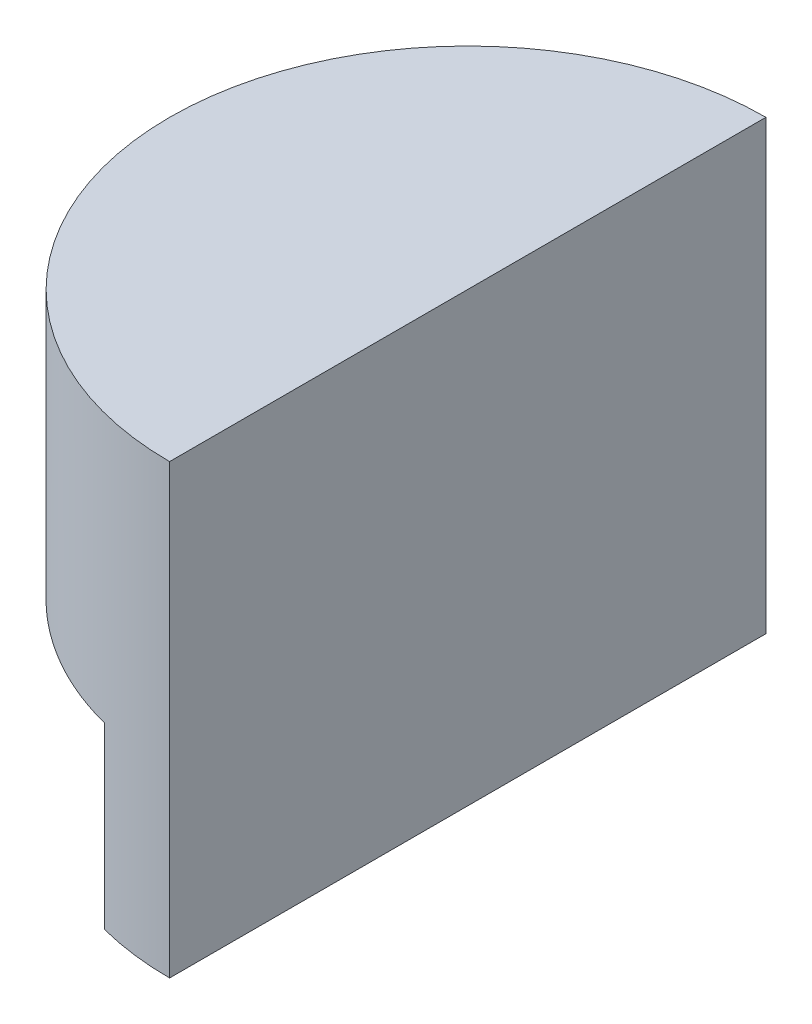
SolidWorks part; units mm, degrees
ref_plane "Alzado" through (0, 0, 0) normal (0, 0, 1) x (1, 0, 0)
ref_plane "Planta" through (0, 0, 0) normal (0, 1, 0) x (1, 0, 0)
ref_plane "Vista lateral" through (0, 0, 0) normal (1, 0, 0) x (0, 0, -1)
sketch "Croquis1" plane through (0, 0, 0) normal (0, 1, 0) x (1, 0, 0)
  line L0 (0, 10) -> (0, -10)
  arc A0 (0, 10) -> (0, -10) centre (0, 0) ccw
  point P3 (0, 0)
  dimension "D1" = 20
extrude "Saliente-Extruir1" add sketch "Croquis1" along normal blind 15
ref_plane "Plano1" through (0, 0, 10) normal (0, 0, 1) x (1, 0, 0)
sketch "Croquis2" plane through (0, 0, 10) normal (0, 0, 1) x (1, 0, 0)
  line L0 (-2.5, 0) -> (-2.5, 6)
  line L1 (-10, 0) -> (0, 0) construction
  line L2 (-2.5, 6) -> (-10, 6)
  line L3 (-10, 15) -> (-10, 0) construction
  line L4 (-10, 6) -> (-10, 0)
  line L5 (-10, 0) -> (-2.5, 0)
  dimension "D1" = 7.5
  dimension "D2" = 6
extrude "Cortar-Extruir2" cut sketch "Croquis2" against normal through all
sketch "Croquis4" plane through (0, 6, 0) normal (0, -1, 0) x (1, 0, 0)
  circle A0 centre (-7.5, 0) radius 2.5
  arc A1 (-2.5, 9.6825) -> (-2.5, -9.6825) centre (0, 0) ccw construction
  point P7 (0, 0)
  dimension "D1" = 5
extrude "Saliente-Extruir2" add sketch "Croquis4" along normal blind 6
